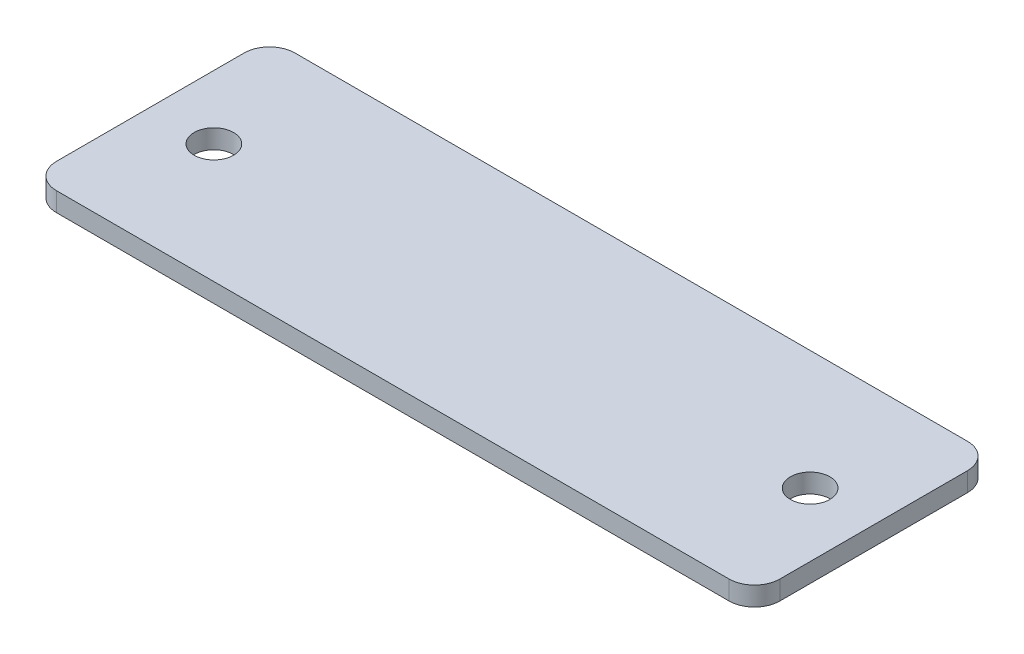
SolidWorks part; units mm, degrees
ref_plane "Front Plane" through (0, 0, 0) normal (0, 0, 1) x (1, 0, 0)
ref_plane "Top Plane" through (0, 0, 0) normal (0, 1, 0) x (1, 0, 0)
ref_plane "Right Plane" through (0, 0, 0) normal (1, 0, 0) x (0, 0, -1)
sketch "Sketch1" plane through (0, 0, 0) normal (0, 1, 0) x (1, 0, 0)
  line L1 (-28.4375, -9.375) -> (28.4375, -9.375)
  line L2 (-28.4375, -9.375) -> (-28.4375, 9.375)
  line L3 (-28.4375, 9.375) -> (28.4375, 9.375)
  line L4 (28.4375, -9.375) -> (28.4375, 9.375)
  line L5 (-28.4375, -9.375) -> (28.4375, 9.375) construction
  line L6 (-28.4375, 9.375) -> (28.4375, -9.375) construction
  point P0 (0, 0)
  dimension "D1" = 56.875
  dimension "D2" = 18.75
extrude "Boss-Extrude1" add sketch "Sketch1" along normal blind 1.5
fillet "Fillet1" radius 2 4 edges at (-28.4375, 0.75, -9.375) (-28.4375, 0.75, 9.375) (28.4375, 0.75, -9.375) (28.4375, 0.75, 9.375)
sketch "Sketch2" plane through (0, 1.5, 0) normal (0, 1, 0) x (1, 0, 0)
  line L0 (28.4375, 0) -> (-28.4375, 0) construction
  line L1 (28.4375, -7.375) -> (28.4375, 7.375) construction
  line L2 (-28.4375, 7.375) -> (-28.4375, -7.375) construction
  circle A0 centre (-23.4375, 0) radius 1.55
  circle A1 centre (23.4375, 0) radius 1.55
  dimension "D3" = 3.1
  dimension "D4" = 3.1
  dimension "D1" = 5
  dimension "D2" = 5
extrude "Cut-Extrude1" cut sketch "Sketch2" against normal blind 1.5
